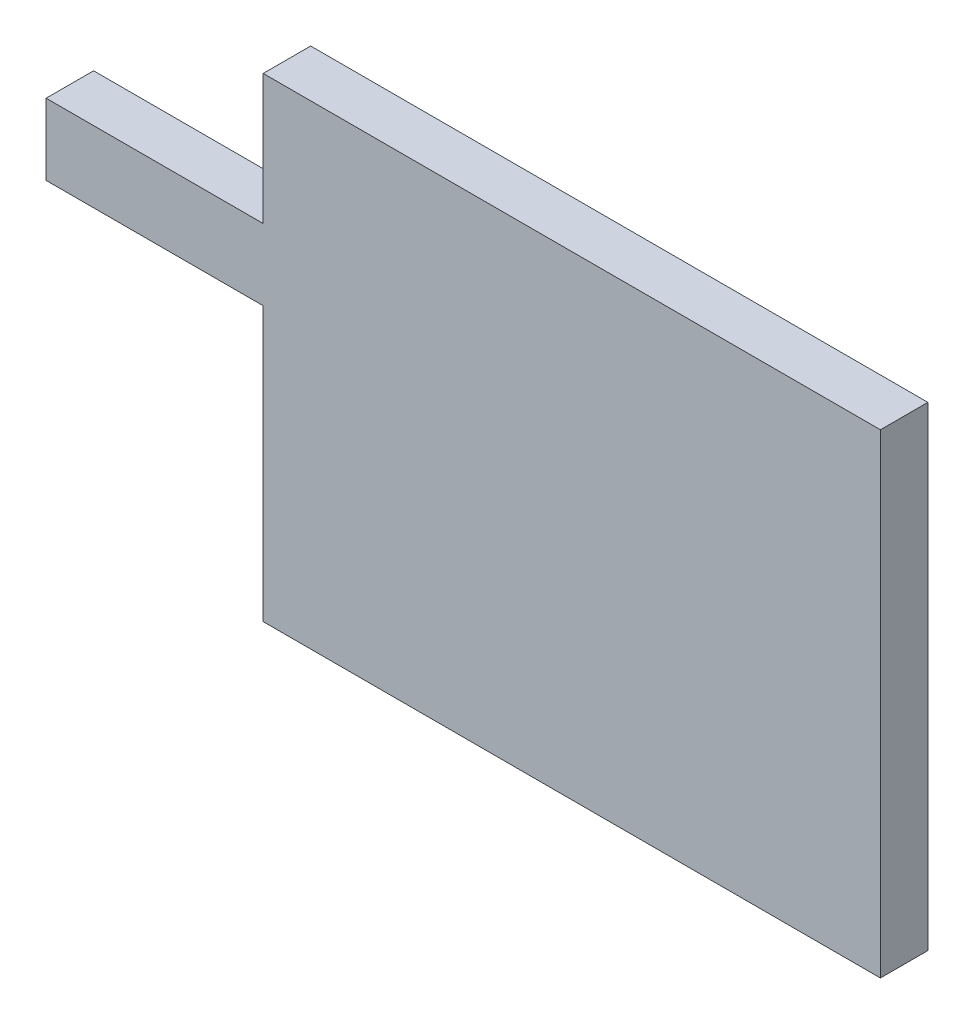
SolidWorks part; units mm, degrees
ref_plane "Front Plane" through (0, 0, 0) normal (0, 0, 1) x (1, 0, 0)
ref_plane "Top Plane" through (0, 0, 0) normal (0, 1, 0) x (1, 0, 0)
ref_plane "Right Plane" through (0, 0, 0) normal (1, 0, 0) x (0, 0, -1)
sketch "Sketch1" plane through (0, 0, 0) normal (0, 0, 1) x (1, 0, 0)
  line L1 (-105.5012, 45.1196) -> (24.4988, 45.1196)
  line L2 (-105.5012, 45.1196) -> (-105.5012, 17.7396)
  line L3 (-105.5012, -54.8804) -> (24.4988, -54.8804)
  line L4 (24.4988, 45.1196) -> (24.4988, -54.8804)
  line L9 (-151.2212, 17.7396) -> (-105.5012, 17.7396)
  line L10 (-151.2212, 17.7396) -> (-151.2212, 2.7396)
  line L11 (-151.2212, 2.7396) -> (-105.5012, 2.7396)
  line L13 (-105.5012, 2.7396) -> (-105.5012, -54.8804)
  dimension "D1" = 45.72
  dimension "D2" = 130
  dimension "D3" = 15
extrude "Boss-Extrude1" add sketch "Sketch1" along normal blind 10
